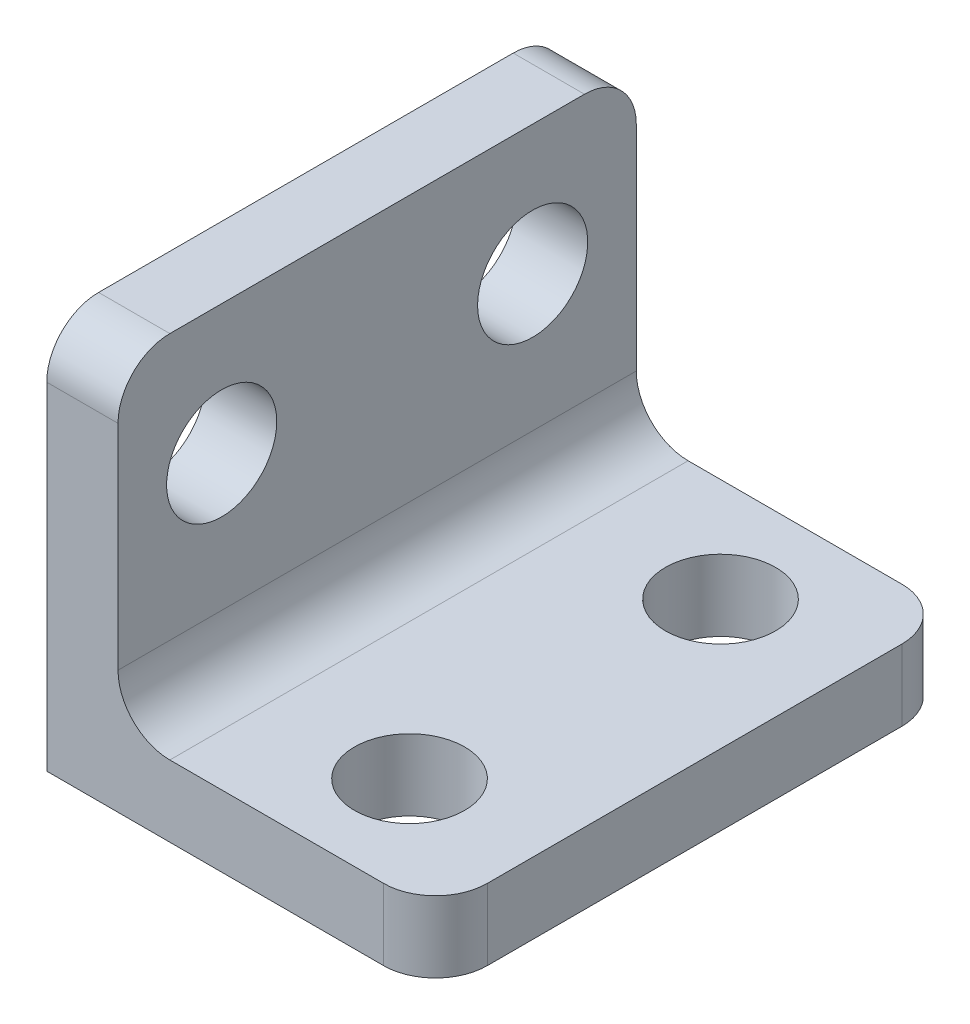
SolidWorks part; units mm, degrees
ref_plane "Front Plane" through (0, 0, 0) normal (0, 0, 1) x (1, 0, 0)
ref_plane "Top Plane" through (0, 0, 0) normal (0, 1, 0) x (1, 0, 0)
ref_plane "Right Plane" through (0, 0, 0) normal (1, 0, 0) x (0, 0, -1)
sketch "Sketch3" plane through (0, 0, 0) normal (0, 1, 0) x (1, 0, 0)
  line L0 (0, -10) -> (15, -10)
  line L1 (0, 0) -> (15, 0) construction
  line L3 (0, 10) -> (15, 10)
  line L4 (15, -10) -> (15, 10)
  line L5 (0, 10) -> (0, -10)
  circle A0 centre (10, 6) radius 2.125
  circle A1 centre (10, -6) radius 2.125
  dimension "D2" = 4.25
  dimension "D1" = 6
  dimension "D3" = 10
  dimension "D4" = 10
  dimension "D5" = 5
extrude "Boss-Extrude3" add sketch "Sketch3" along normal blind 2.75
sketch "Sketch5" plane through (0, 0, 0) normal (-1, 0, 0) x (0, 0, 1)
  line L0 (0, 15) -> (0, 0.1839) construction
  line L1 (-10, 0) -> (10, 0)
  line L2 (-10, 0) -> (-10, 15)
  line L3 (-10, 15) -> (10, 15)
  line L4 (10, 0) -> (10, 15)
  circle A0 centre (-6, 10) radius 2.125
  circle A1 centre (6, 10) radius 2.125
  dimension "D1" = 4.25
  dimension "D2" = 5
  dimension "D3" = 6
  dimension "D4" = 10
extrude "Boss-Extrude5" add sketch "Sketch5" against normal blind 2.75
fillet "Fillet4" radius 2 5 edges at (15, 1.375, -10) (15, 1.375, 10) (1.375, 15, -10) (1.375, 15, 10) (2.75, 2.75, 0)
